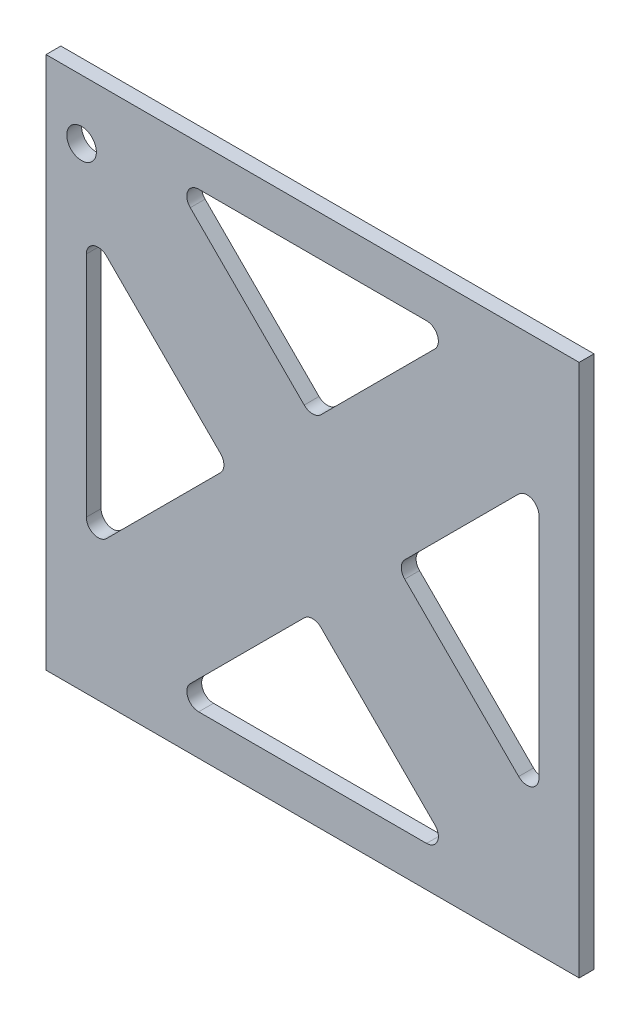
SolidWorks part; units mm, degrees
ref_plane "Front Plane" through (0, 0, 0) normal (0, 0, 1) x (1, 0, 0)
ref_plane "Top Plane" through (0, 0, 0) normal (0, 1, 0) x (1, 0, 0)
ref_plane "Right Plane" through (0, 0, 0) normal (1, 0, 0) x (0, 0, -1)
sketch "Sketch1" plane through (0, 0, 0) normal (0, 0, 1) x (1, 0, 0)
  line L5 (-57.15, -57.15) -> (57.15, -57.15)
  line L6 (-57.15, -57.15) -> (-57.15, 57.15)
  line L7 (-57.15, 57.15) -> (57.15, 57.15)
  line L13 (57.15, -57.15) -> (57.15, 57.15)
  line L23 (-57.15, -57.15) -> (-49.7355, -49.7355) construction
  line L25 (-24.4252, -48.5178) -> (24.4252, -48.5178)
  line L41 (49.7355, 49.7355) -> (57.15, 57.15) construction
  line L44 (-1.7961, -19.7566) -> (-26.2212, -44.1818)
  line L45 (-57.15, 57.15) -> (57.15, -57.15) construction
  line L46 (1.7961, -19.7566) -> (26.2212, -44.1818)
  line L48 (0, -48.5178) -> (0, -34.0814) construction
  line L49 (-48.5178, 24.4252) -> (-48.5178, -24.4252)
  line L50 (-19.7566, 1.7961) -> (-44.1818, 26.2212)
  line L51 (-19.7566, -1.7961) -> (-44.1818, -26.2212)
  line L52 (-48.5178, 0) -> (-34.0814, 0) construction
  line L53 (24.4252, 48.5178) -> (-24.4252, 48.5178)
  line L54 (1.7961, 19.7566) -> (26.2212, 44.1818)
  line L55 (-1.7961, 19.7566) -> (-26.2212, 44.1818)
  line L56 (0, 48.5178) -> (0, 34.0814) construction
  line L57 (48.5178, -24.4252) -> (48.5178, 24.4252)
  line L58 (19.7566, -1.7961) -> (44.1818, -26.2212)
  line L59 (19.7566, 1.7961) -> (44.1818, 26.2212)
  line L60 (48.5178, 0) -> (34.0814, 0) construction
  circle A27 centre (-49.53, 44.45) radius 3.175
  arc A34 (24.4252, -48.5178) -> (26.2212, -44.1818) centre (24.4252, -45.9778) ccw
  arc A35 (-26.2212, -44.1818) -> (-24.4252, -48.5178) centre (-24.4252, -45.9778) ccw
  arc A36 (-1.7961, -19.7566) -> (1.7961, -19.7566) centre (0, -21.5526) cw
  arc A40 (-48.5178, -24.4252) -> (-44.1818, -26.2212) centre (-45.9778, -24.4252) ccw
  arc A41 (-44.1818, 26.2212) -> (-48.5178, 24.4252) centre (-45.9778, 24.4252) ccw
  arc A42 (-19.7566, 1.7961) -> (-19.7566, -1.7961) centre (-21.5526, 0) cw
  arc A43 (-24.4252, 48.5178) -> (-26.2212, 44.1818) centre (-24.4252, 45.9778) ccw
  arc A44 (26.2212, 44.1818) -> (24.4252, 48.5178) centre (24.4252, 45.9778) ccw
  arc A45 (1.7961, 19.7566) -> (-1.7961, 19.7566) centre (0, 21.5526) cw
  arc A46 (48.5178, 24.4252) -> (44.1818, 26.2212) centre (45.9778, 24.4252) ccw
  arc A47 (44.1818, -26.2212) -> (48.5178, -24.4252) centre (45.9778, -24.4252) ccw
  arc A48 (19.7566, -1.7961) -> (19.7566, 1.7961) centre (21.5526, 0) cw
  point P0 (0, 0)
  point P8 (0, 0)
  point P9 (0, 0)
  point P18 (0, 0)
  point P46 (0, -17.9605)
  point P60 (0, 0)
  dimension "D3" = 12.7
  dimension "D4" = 6.35
  dimension "D6" = 12.7
  dimension "D7" = 8.6322
  dimension "D8" = 4
  dimension "D5" = 2.54
  dimension "D1" = 7.62
  dimension "D2" = 114.3
extrude "Boss-Extrude2" add sketch "Sketch1" along normal mid plane 3.175
sketch "Sketch2" plane through (0, 0, -1.5875) normal (0, 0, -1) x (-1, 0, 0)
  line L0 (57.15, 44.45) -> (63.5, 44.45)
  line L1 (63.5, 44.45) -> (63.5, 19.05)
  line L2 (63.5, 19.05) -> (57.15, 19.05)
  line L3 (57.15, 57.15) -> (57.15, -57.15) construction
  line L4 (57.15, 19.05) -> (57.15, 44.45)
  line L5 (-57.15, 57.15) -> (57.15, 57.15) construction
  dimension "D1" = 12.7
  dimension "D2" = 6.35
  dimension "D3" = 25.4
extrude "Boss-Extrude3" [suppressed] add sketch "Sketch2" against normal blind 3.175
